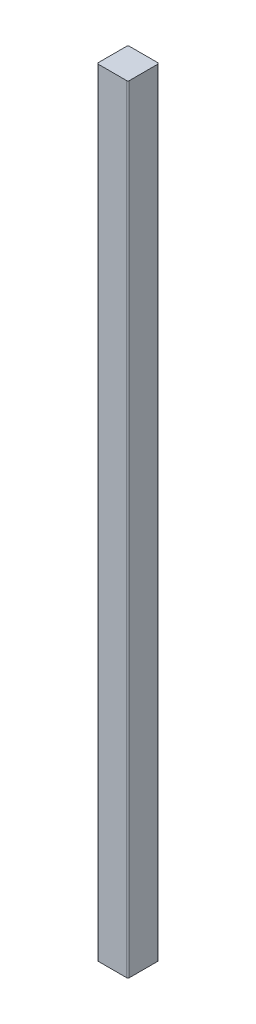
SolidWorks part; units mm, degrees
material "6063-O, Extruded Rod (SS)"
ref_plane "Front Plane" through (0, 0, 0) normal (0, 0, 1) x (1, 0, 0)
ref_plane "Top Plane" through (0, 0, 0) normal (0, 1, 0) x (1, 0, 0)
ref_plane "Right Plane" through (0, 0, 0) normal (1, 0, 0) x (0, 0, -1)
sketch "Sketch1" plane through (0, 0, 0) normal (0, 1, 0) x (1, 0, 0)
  line L1 (-18, 20) -> (18, 20)
  line L2 (-20, 18) -> (-20, -18)
  line L3 (-18, -20) -> (18, -20)
  line L4 (20, 18) -> (20, -18)
  line L5 (-20, 20) -> (20, -20) construction
  line L6 (-20, -20) -> (20, 20) construction
  arc A0 (-20, -18) -> (-18, -20) centre (-18, -18) ccw
  arc A1 (18, -20) -> (20, -18) centre (18, -18) ccw
  arc A2 (18, 20) -> (20, 18) centre (18, 18) cw
  arc A3 (-18, 20) -> (-20, 18) centre (-18, 18) ccw
  point P0 (0, 0)
  dimension "D3" = 2
  dimension "D1" = 40
  dimension "D2" = 40
extrude "Boss-Extrude1" add sketch "Sketch1" along normal blind 1000
